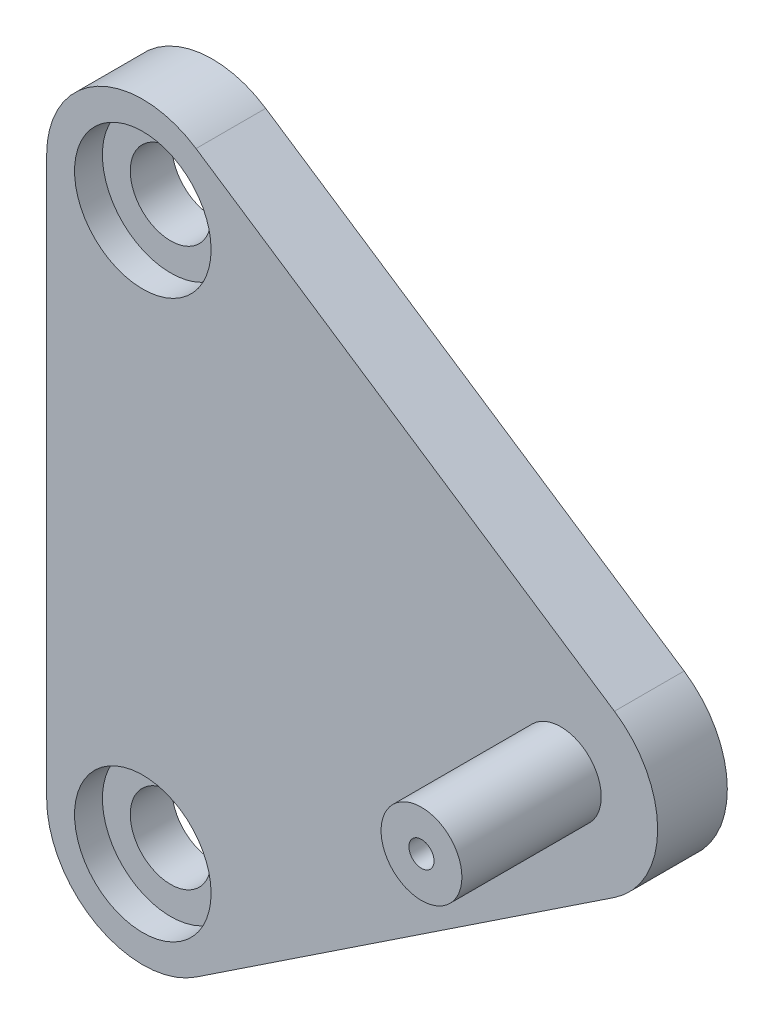
SolidWorks part; units mm, degrees
ref_plane "Alzado" through (0, 0, 0) normal (0, 0, 1) x (1, 0, 0)
ref_plane "Planta" through (0, 0, 0) normal (0, 1, 0) x (1, 0, 0)
ref_plane "Vista lateral" through (0, 0, 0) normal (1, 0, 0) x (0, 0, -1)
sketch "Croquis1" plane through (0, 0, 0) normal (0, 0, 1) x (1, 0, 0)
  line L0 (0, 0) -> (26.4845, 0) construction
  line L1 (-3.45, 10) -> (-3.45, -10)
  line L2 (1.9097, 12.8732) -> (16.9236, 2.894)
  line L3 (1.9097, -12.8732) -> (16.9236, -2.894)
  circle A0 centre (0, 10) radius 1.45
  circle A1 centre (0, -10) radius 1.45
  circle A2 centre (15, 0) radius 1.475 construction
  arc A3 (16.9236, -2.894) -> (16.9236, 2.894) centre (15, 0) ccw
  arc A4 (1.9097, 12.8732) -> (-3.45, 10) centre (0, 10) ccw
  arc A5 (1.9097, -12.8732) -> (-3.45, -10) centre (0, -10) cw
  circle A7 centre (0, 10) radius 3.45 construction
  circle A8 centre (15, 0) radius 3.475 construction
  circle A9 centre (0, -10) radius 3.45 construction
  point P10 (3.45, -10)
  point P12 (18.475, 0)
  point P21 (3.45, 10)
  dimension "D1" = 2.9
  dimension "D3" = 2.95
  dimension "D2" = 10
  dimension "D4" = 15
  dimension "D5" = 2
  dimension "D6" = 2
extrude "Saliente-Extruir1" add sketch "Croquis1" along normal blind 2.5
sketch "Croquis2" plane through (0, 0, 2.5) normal (0, 0, 1) x (1, 0, 0)
  circle A2 centre (0, 10) radius 2.45
  circle A3 centre (0, 10) radius 2.45
  circle A5 centre (0, -10) radius 2.45
  circle A6 centre (0, -10) radius 2.45
  dimension "D1" = 1
  dimension "D2" = 1
extrude "Cortar-Extruir1" cut sketch "Croquis2" against normal blind 1
sketch "Croquis3" plane through (0, 0, 2.5) normal (0, 0, 1) x (1, 0, 0)
  circle A0 centre (15, 0) radius 1.45
  circle A1 centre (15, 0) radius 0.45
  dimension "D1" = 2.9
  dimension "D2" = 1
extrude "Saliente-Extruir2" add sketch "Croquis3" along normal blind 5
sketch "Croquis4" plane through (0, 0, 2.5) normal (0, 0, 1) x (1, 0, 0)
  circle A1 centre (15, 0) radius 0.45
  circle A2 centre (15, 0) radius 0.45
  dimension "D1" = 0
extrude "Cortar-Extruir2" cut sketch "Croquis4" against normal through all
